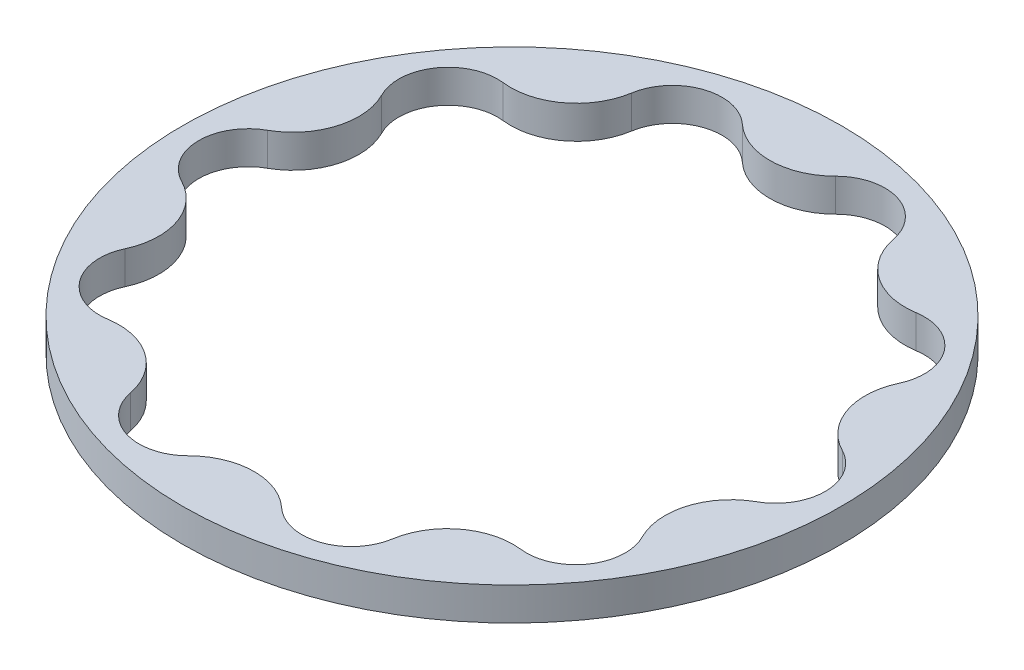
SolidWorks part; units mm, degrees
ref_plane "Front Plane" through (0, 0, 0) normal (0, 0, 1) x (1, 0, 0)
ref_plane "Top Plane" through (0, 0, 0) normal (0, 1, 0) x (1, 0, 0)
ref_plane "Right Plane" through (0, 0, 0) normal (1, 0, 0) x (0, 0, -1)
sketch "Sketch1" plane through (0, 0, 0) normal (0, 1, 0) x (1, 0, 0)
  line L0 (12.3601, 85.8397) -> (0, 0) construction
  line L1 (0, 0) -> (60.4548, 62.1807) construction
  circle A0 centre (0, 0) radius 100
  circle A1 centre (0, 0) radius 86.725 construction
  circle A2 centre (0, 0) radius 78.65 construction
  arc A3 (12.3601, 85.8397) -> (37.6775, 78.1129) centre (22.9582, 75.2246) cw
  arc A4 (37.6775, 78.1129) -> (60.4548, 62.1807) centre (57.3367, 81.9706) ccw
  arc A5 (60.4548, 62.1807) -> (76.3954, 41.0484) centre (62.7895, 47.3635) cw
  arc A6 (76.3954, 41.0484) -> (85.4579, 14.7708) centre (94.5674, 32.6139) ccw
  arc A7 (85.4579, 14.7708) -> (85.9328, -11.6952) centre (78.6373, 1.4111) cw
  arc A8 (85.9328, -11.6952) -> (77.8189, -38.2811) centre (95.6767, -29.2001) ccw
  arc A9 (77.8189, -38.2811) -> (62.6468, -59.9717) centre (64.4484, -45.0803) cw
  arc A10 (62.6468, -59.9717) -> (40.4558, -76.7109) centre (60.2406, -79.8607) ccw
  arc A11 (40.4558, -76.7109) -> (15.4319, -85.341) centre (25.6423, -74.3525) cw
  arc A12 (15.4319, -85.341) -> (-12.3601, -85.8397) centre (1.7948, -100.0172) ccw
  arc A13 (-12.3601, -85.8397) -> (-37.6775, -78.1129) centre (-22.9582, -75.2246) cw
  arc A14 (-37.6775, -78.1129) -> (-60.4548, -62.1807) centre (-57.3367, -81.9706) ccw
  arc A15 (-60.4548, -62.1807) -> (-76.3954, -41.0484) centre (-62.7895, -47.3635) cw
  arc A16 (-76.3954, -41.0484) -> (-85.4579, -14.7708) centre (-94.5674, -32.6139) ccw
  arc A17 (-85.4579, -14.7708) -> (-85.9328, 11.6952) centre (-78.6373, -1.4111) cw
  arc A18 (-85.9328, 11.6952) -> (-77.8189, 38.2811) centre (-95.6767, 29.2001) ccw
  arc A19 (-77.8189, 38.2811) -> (-62.6468, 59.9717) centre (-64.4484, 45.0803) cw
  arc A20 (-62.6468, 59.9717) -> (-40.4558, 76.7109) centre (-60.2406, 79.8607) ccw
  arc A21 (-40.4558, 76.7109) -> (-15.4319, 85.341) centre (-25.6423, 74.3525) cw
  arc A22 (-15.4319, 85.341) -> (12.3601, 85.8397) centre (-1.7948, 100.0172) ccw
  point P10 (0, 0)
  point P58 (0, 0)
  dimension "D1" = 200
  dimension "D2" = 157.3
  dimension "D3" = 173.45
  dimension "D4" = 15
  dimension "D5" = 36
  dimension "D7" = 1.7948
  dimension "D6" = 10
extrude "Boss-Extrude1" add sketch "Sketch1" along normal blind 10 contours A0 A21 A22 A3 A4 A5 A6 A7 A8 A9 A10 A11 A12 A13 A14 A15 A16 A17 A18 A19 A20
